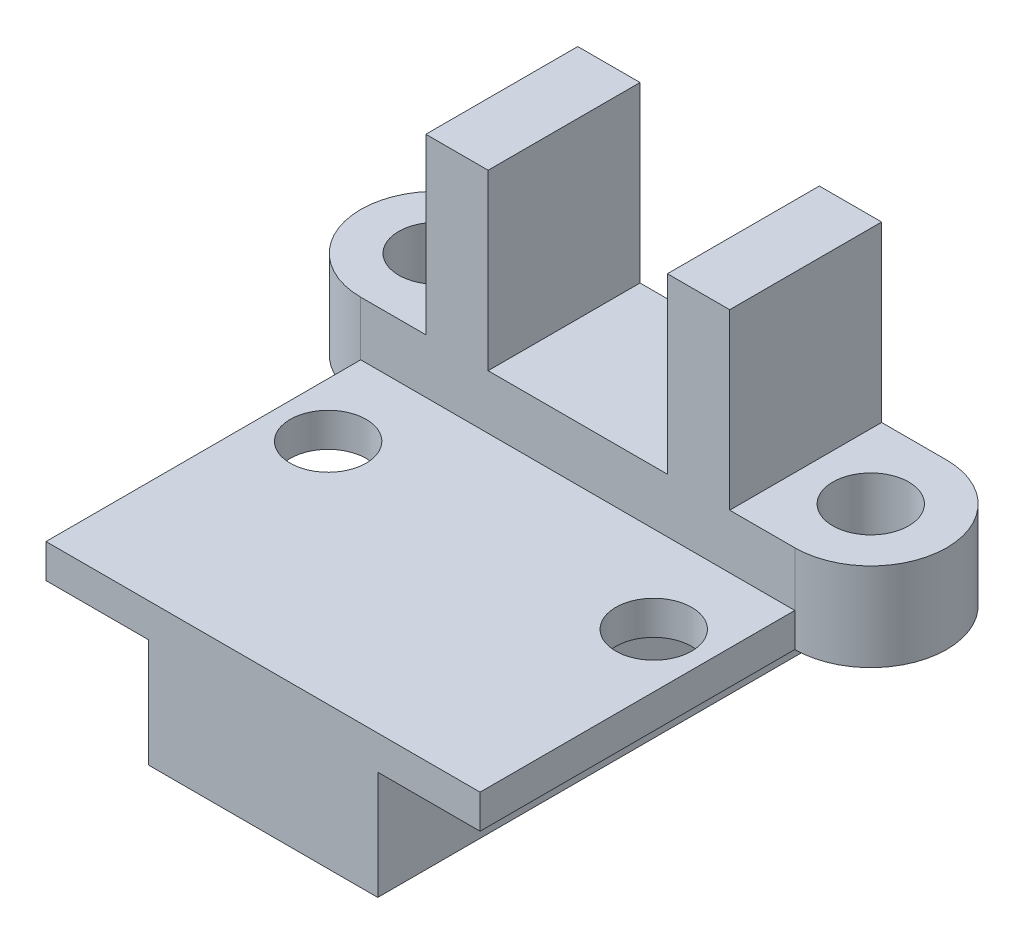
SolidWorks part; units mm, degrees
ref_plane "Front Plane" through (0, 0, 0) normal (0, 0, 1) x (1, 0, 0)
ref_plane "Top Plane" through (0, 0, 0) normal (0, 1, 0) x (1, 0, 0)
ref_plane "Right Plane" through (0, 0, 0) normal (1, 0, 0) x (0, 0, -1)
sketch "Sketch1" plane through (0, 0, 0) normal (0, 1, 0) x (1, 0, 0)
  line L0 (-10, 14.25) -> (10, 14.25)
  line L1 (-10, -7.25) -> (10, -7.25)
  line L2 (-10, -7.25) -> (-10, 7.25)
  line L4 (10, -7.25) -> (10, 7.25)
  circle A0 centre (-10, 10.75) radius 1.75
  circle A1 centre (10, 10.75) radius 1.75
  arc A2 (-10, 14.25) -> (-10, 7.25) centre (-10, 10.75) ccw
  arc A3 (10, 7.25) -> (10, 14.25) centre (10, 10.75) ccw
  circle A4 centre (-7.5, 3.25) radius 1.75
  circle A5 centre (7.5, 3.25) radius 1.75
  point P0 (0, 0)
  dimension "D3" = 3.5
  dimension "D4" = 3.5
  dimension "D5" = 3.5
  dimension "D6" = 3.5
  dimension "D1" = 20
  dimension "D2" = 14.5
  dimension "D7" = 2.5
  dimension "D8" = 2.5
  dimension "D9" = 10.5
  dimension "D10" = 10.5
extrude "Boss-Extrude1" add sketch "Sketch1" along normal blind 1.56
sketch "Sketch2" plane through (0, 1.56, 0) normal (0, 1, 0) x (1, 0, 0)
  line L2 (-10, 10.75) -> (10, 10.75) construction
  line L3 (-10, 14.25) -> (10, 14.25)
  line L4 (-10, 7.25) -> (10, 7.25)
  arc A0 (-10, 14.25) -> (-10, 7.25) centre (-10, 10.75) ccw
  arc A1 (10, 7.25) -> (10, 14.25) centre (10, 10.75) ccw
  circle A2 centre (-10, 10.75) radius 1.75
  circle A3 centre (10, 10.75) radius 1.75
  point P8 (0, 10.75)
  dimension "D1" = 7
extrude "Boss-Extrude2" add sketch "Sketch2" along normal blind 2.5
sketch "Sketch3" plane through (0, 4.06, 0) normal (0, 1, 0) x (1, 0, 0)
  line L1 (-10, 7.25) -> (10, 7.25) construction
  line L3 (-7, 7.25) -> (7, 7.25)
  line L4 (-7, 7.25) -> (-7, 14.25)
  line L5 (-7, 14.25) -> (7, 14.25)
  line L6 (7, 7.25) -> (7, 14.25)
  line L7 (-7, 7.25) -> (7, 14.25) construction
  line L8 (-7, 14.25) -> (7, 7.25) construction
  point P6 (0, 10.75)
  dimension "D1" = 7
  dimension "D2" = 3.5
  dimension "D3" = 14
extrude "Boss-Extrude3" add sketch "Sketch3" along normal blind 8
sketch "Sketch4" plane through (0, 12.06, 0) normal (0, 1, 0) x (1, 0, 0)
  line L2 (7, 14.25) -> (-7, 14.25) construction
  line L3 (-4.13, 7.25) -> (4.13, 7.25)
  line L4 (-4.13, 7.25) -> (-4.13, 14.25)
  line L5 (-4.13, 14.25) -> (4.13, 14.25)
  line L6 (4.13, 7.25) -> (4.13, 14.25)
  line L7 (-4.13, 7.25) -> (4.13, 14.25) construction
  line L8 (-4.13, 14.25) -> (4.13, 7.25) construction
  point P7 (0, 10.75)
  dimension "D1" = 8.26
extrude "Cut-Extrude1" cut sketch "Sketch4" against normal blind 8
sketch "Sketch5" plane through (0, 0, 0) normal (0, -1, 0) x (1, 0, 0)
  line L0 (-10, 7.25) -> (10, 7.25) construction
  line L1 (-5.286, -7.25) -> (-5.286, -14.25)
  line L2 (-5.286, -7.25) -> (-5.286, 7.25)
  line L3 (-5.286, 7.25) -> (5.286, 7.25)
  line L4 (5.286, -7.25) -> (5.286, 7.25)
  line L5 (-5.286, -7.25) -> (5.286, 7.25) construction
  line L6 (-5.286, 7.25) -> (5.286, -7.25) construction
  line L7 (10, -14.25) -> (-10, -14.25) construction
  line L8 (-5.286, -14.25) -> (5.286, -14.25)
  line L9 (5.286, -14.25) -> (5.286, -7.25)
  point P0 (0, 0)
extrude "Boss-Extrude4" add sketch "Sketch5" along normal blind 5
